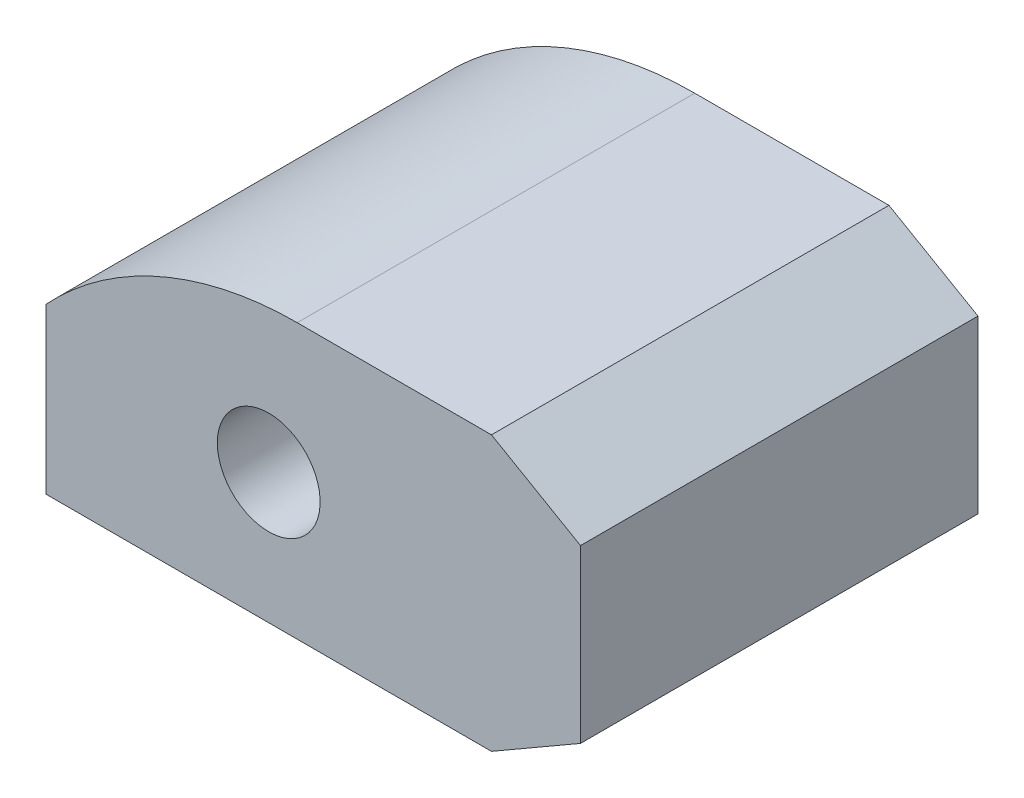
SolidWorks part; units mm, degrees
material "1060 Alloy"
ref_plane "Front Plane" through (0, 0, 0) normal (0, 0, 1) x (1, 0, 0)
ref_plane "Top Plane" through (0, 0, 0) normal (0, 1, 0) x (1, 0, 0)
ref_plane "Right Plane" through (0, 0, 0) normal (1, 0, 0) x (0, 0, -1)
sketch "Sketch1" plane through (0, 0, 0) normal (0, 0, 1) x (1, 0, 0)
  line L0 (0, 13.8138) -> (0, -28.7241) construction
  line L1 (32.5, -19) -> (-32.5, -19)
  line L2 (-32.5, -19) -> (-32.5, 5)
  line L3 (32.5, -19) -> (45.4904, -11.5)
  line L4 (45.4904, -11.5) -> (45.4904, 13.5)
  line L5 (45.4904, 13.5) -> (32.5, 21)
  line L6 (32.5, 21) -> (4.1606, 21)
  circle A0 centre (0, 0) radius 7.5
  arc A1 (-32.5, 5) -> (4.1606, 21) centre (4.1606, -29) cw
  point P8 (0, -19)
  dimension "D1" = 15
  dimension "D9" = 50
  dimension "D2" = 65
  dimension "D3" = 19
  dimension "D4" = 24
  dimension "D5" = 15
  dimension "D6" = 30
  dimension "D7" = 30
  dimension "D8" = 40
extrude "Boss-Extrude1" add sketch "Sketch1" along normal blind 58
equation "\"A\" = 58mm"
equation "\"B\"= 40mm"
equation "\"C\"= 65mm"
equation "\"D2@Sketch1\"=\"C\""
equation "\"D8@Sketch1\"=\"B\""
